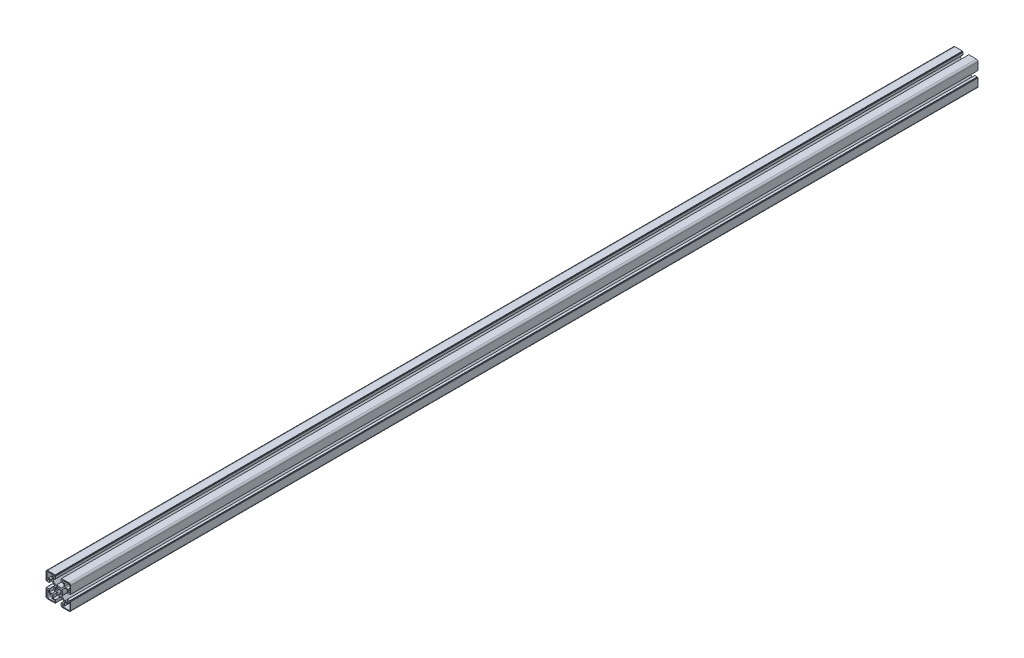
SolidWorks part; units mm, degrees
ref_plane "Front Plane" through (0, 0, 0) normal (0, 0, 1) x (1, 0, 0)
ref_plane "Top Plane" through (0, 0, 0) normal (0, 1, 0) x (1, 0, 0)
ref_plane "Right Plane" through (0, 0, 0) normal (1, 0, 0) x (0, 0, -1)
sketch "Sketch1" plane through (0, 0, 0) normal (0, 0, 1) x (1, 0, 0)
  line L2 (-19.5072, 22.5044) -> (-5.7912, 22.5044)
  line L3 (-5.7912, 22.5044) -> (-5.7912, 21.0058)
  line L4 (-5.7912, 21.0058) -> (-5.0038, 21.0058)
  line L6 (-5.0038, 21.0058) -> (-5.0038, 16.51)
  line L7 (-5.0038, 16.51) -> (-10.0457, 16.51)
  line L8 (-10.0457, 16.51) -> (-10.0457, 11.6801)
  line L9 (-10.0457, 11.6801) -> (-4.781, 6.4154)
  line L11 (-11.6801, 10.0457) -> (-6.4154, 4.781)
  line L12 (-16.51, 10.0457) -> (-11.6801, 10.0457)
  line L13 (-16.51, 5.0038) -> (-16.51, 10.0457)
  line L14 (-21.0058, 5.0038) -> (-16.51, 5.0038)
  line L15 (-21.0058, 5.7912) -> (-21.0058, 5.0038)
  line L16 (-22.5044, 5.7912) -> (-21.0058, 5.7912)
  line L17 (-22.5044, 19.5072) -> (-22.5044, 5.7912)
  line L18 (-18.0086, 11.5443) -> (-13.0429, 11.5443)
  line L19 (-18.0086, 11.5443) -> (-18.0086, 8.7884)
  line L20 (-11.5443, 18.0086) -> (-11.5443, 13.0429)
  line L21 (-21.0058, 19.5072) -> (-21.0058, 8.7884)
  line L23 (-11.5443, 18.0086) -> (-8.7884, 18.0086)
  line L24 (-19.5072, 21.0058) -> (-8.7884, 21.0058)
  line L25 (1.1893, 5.9789) -> (0.9762, 4.9077)
  line L26 (-1.1893, 5.9789) -> (-0.9762, 4.9077)
  line L27 (5.0686, 3.3868) -> (4.1605, 2.78)
  line L28 (3.3868, 5.0686) -> (2.78, 4.1605)
  line L29 (5.9789, -1.1893) -> (4.9077, -0.9762)
  line L30 (5.9789, 1.1893) -> (4.9077, 0.9762)
  line L31 (3.3868, -5.0686) -> (2.78, -4.1605)
  line L32 (5.0686, -3.3868) -> (4.1605, -2.78)
  line L33 (-1.1893, -5.9789) -> (-0.9762, -4.9077)
  line L34 (1.1893, -5.9789) -> (0.9762, -4.9077)
  line L35 (-5.0686, -3.3868) -> (-4.1605, -2.78)
  line L36 (-3.3868, -5.0686) -> (-2.78, -4.1605)
  line L37 (-5.9789, 1.1893) -> (-4.9077, 0.9762)
  line L38 (-5.9789, -1.1893) -> (-4.9077, -0.9762)
  line L39 (-3.3868, 5.0686) -> (-2.78, 4.1605)
  line L40 (-5.0686, 3.3868) -> (-4.1605, 2.78)
  line L41 (11.5443, 18.0086) -> (8.7884, 18.0086)
  line L42 (19.5072, 21.0058) -> (8.7884, 21.0058)
  line L43 (19.5072, 22.5044) -> (5.7912, 22.5044)
  line L44 (5.7912, 22.5044) -> (5.7912, 21.0058)
  line L45 (5.7912, 21.0058) -> (5.0038, 21.0058)
  line L46 (5.0038, 21.0058) -> (5.0038, 16.51)
  line L47 (5.0038, 16.51) -> (10.0457, 16.51)
  line L48 (10.0457, 16.51) -> (10.0457, 11.6801)
  line L49 (10.0457, 11.6801) -> (4.781, 6.4154)
  line L50 (11.6801, 10.0457) -> (6.4154, 4.781)
  line L51 (21.0058, 19.5072) -> (21.0058, 8.7884)
  line L52 (11.5443, 18.0086) -> (11.5443, 13.0429)
  line L53 (18.0086, 11.5443) -> (18.0086, 8.7884)
  line L54 (18.0086, 11.5443) -> (13.0429, 11.5443)
  line L55 (22.5044, 19.5072) -> (22.5044, 5.7912)
  line L56 (22.5044, 5.7912) -> (21.0058, 5.7912)
  line L57 (21.0058, 5.7912) -> (21.0058, 5.0038)
  line L58 (21.0058, 5.0038) -> (16.51, 5.0038)
  line L59 (16.51, 5.0038) -> (16.51, 10.0457)
  line L60 (16.51, 10.0457) -> (11.6801, 10.0457)
  line L61 (16.51, -10.0457) -> (11.6801, -10.0457)
  line L62 (16.51, -5.0038) -> (16.51, -10.0457)
  line L63 (21.0058, -5.0038) -> (16.51, -5.0038)
  line L64 (21.0058, -5.7912) -> (21.0058, -5.0038)
  line L65 (22.5044, -5.7912) -> (21.0058, -5.7912)
  line L66 (22.5044, -19.5072) -> (22.5044, -5.7912)
  line L67 (18.0086, -11.5443) -> (13.0429, -11.5443)
  line L68 (18.0086, -11.5443) -> (18.0086, -8.7884)
  line L69 (11.5443, -18.0086) -> (11.5443, -13.0429)
  line L70 (21.0058, -19.5072) -> (21.0058, -8.7884)
  line L71 (11.6801, -10.0457) -> (6.4154, -4.781)
  line L72 (10.0457, -11.6801) -> (4.781, -6.4154)
  line L73 (10.0457, -16.51) -> (10.0457, -11.6801)
  line L74 (5.0038, -16.51) -> (10.0457, -16.51)
  line L75 (5.0038, -21.0058) -> (5.0038, -16.51)
  line L76 (5.7912, -21.0058) -> (5.0038, -21.0058)
  line L77 (5.7912, -22.5044) -> (5.7912, -21.0058)
  line L78 (19.5072, -22.5044) -> (5.7912, -22.5044)
  line L79 (19.5072, -21.0058) -> (8.7884, -21.0058)
  line L80 (11.5443, -18.0086) -> (8.7884, -18.0086)
  line L81 (-11.5443, -18.0086) -> (-8.7884, -18.0086)
  line L82 (-19.5072, -21.0058) -> (-8.7884, -21.0058)
  line L83 (-19.5072, -22.5044) -> (-5.7912, -22.5044)
  line L84 (-5.7912, -22.5044) -> (-5.7912, -21.0058)
  line L85 (-5.7912, -21.0058) -> (-5.0038, -21.0058)
  line L86 (-5.0038, -21.0058) -> (-5.0038, -16.51)
  line L87 (-5.0038, -16.51) -> (-10.0457, -16.51)
  line L88 (-10.0457, -16.51) -> (-10.0457, -11.6801)
  line L89 (-10.0457, -11.6801) -> (-4.781, -6.4154)
  line L90 (-11.6801, -10.0457) -> (-6.4154, -4.781)
  line L91 (-21.0058, -19.5072) -> (-21.0058, -8.7884)
  line L92 (-11.5443, -18.0086) -> (-11.5443, -13.0429)
  line L93 (-18.0086, -11.5443) -> (-18.0086, -8.7884)
  line L94 (-18.0086, -11.5443) -> (-13.0429, -11.5443)
  line L95 (-22.5044, -19.5072) -> (-22.5044, -5.7912)
  line L96 (-22.5044, -5.7912) -> (-21.0058, -5.7912)
  line L97 (-21.0058, -5.7912) -> (-21.0058, -5.0038)
  line L98 (-21.0058, -5.0038) -> (-16.51, -5.0038)
  line L99 (-16.51, -5.0038) -> (-16.51, -10.0457)
  line L100 (-16.51, -10.0457) -> (-11.6801, -10.0457)
  arc A0 (-22.5044, 19.5072) -> (-19.5072, 22.5044) centre (-19.5072, 19.5072) cw
  arc A1 (-21.0058, 8.7884) -> (-18.0086, 8.7884) centre (-19.5072, 8.7884) ccw
  arc A2 (-21.0058, 19.5072) -> (-19.5072, 21.0058) centre (-19.5072, 19.5072) cw
  arc A3 (-8.7884, 21.0058) -> (-8.7884, 18.0086) centre (-8.7884, 19.5072) cw
  arc A4 (-11.5443, 13.0429) -> (-13.0429, 11.5443) centre (-13.0429, 13.0429) cw
  arc A5 (6.4154, -4.781) -> (6.4154, 4.781) centre (0, 0) ccw
  arc A6 (0.9762, 4.9077) -> (-0.9762, 4.9077) centre (0, 0) ccw
  arc A7 (-5.0686, 3.3868) -> (-5.9789, 1.1893) centre (0, 0) ccw
  arc A8 (4.1605, 2.78) -> (2.78, 4.1605) centre (0, 0) ccw
  arc A9 (4.9077, -0.9762) -> (4.9077, 0.9762) centre (0, 0) ccw
  arc A10 (2.78, -4.1605) -> (4.1605, -2.78) centre (0, 0) ccw
  arc A11 (-0.9762, -4.9077) -> (0.9762, -4.9077) centre (0, 0) ccw
  arc A12 (-4.1605, -2.78) -> (-2.78, -4.1605) centre (0, 0) ccw
  arc A13 (-4.9077, 0.9762) -> (-4.9077, -0.9762) centre (0, 0) ccw
  arc A14 (-2.78, 4.1605) -> (-4.1605, 2.78) centre (0, 0) ccw
  arc A15 (-5.9789, -1.1893) -> (-5.0686, -3.3868) centre (0, 0) ccw
  arc A16 (-3.3868, -5.0686) -> (-1.1893, -5.9789) centre (0, 0) ccw
  arc A17 (1.1893, -5.9789) -> (3.3868, -5.0686) centre (0, 0) ccw
  arc A18 (5.0686, -3.3868) -> (5.9789, -1.1893) centre (0, 0) ccw
  arc A19 (5.9789, 1.1893) -> (5.0686, 3.3868) centre (0, 0) ccw
  arc A20 (3.3868, 5.0686) -> (1.1893, 5.9789) centre (0, 0) ccw
  arc A21 (-1.1893, 5.9789) -> (-3.3868, 5.0686) centre (0, 0) ccw
  arc A22 (8.7884, 21.0058) -> (8.7884, 18.0086) centre (8.7884, 19.5072) ccw
  arc A23 (21.0058, 19.5072) -> (19.5072, 21.0058) centre (19.5072, 19.5072) ccw
  arc A24 (22.5044, 19.5072) -> (19.5072, 22.5044) centre (19.5072, 19.5072) ccw
  arc A25 (11.5443, 13.0429) -> (13.0429, 11.5443) centre (13.0429, 13.0429) ccw
  arc A26 (21.0058, 8.7884) -> (18.0086, 8.7884) centre (19.5072, 8.7884) cw
  arc A27 (21.0058, -8.7884) -> (18.0086, -8.7884) centre (19.5072, -8.7884) ccw
  arc A28 (11.5443, -13.0429) -> (13.0429, -11.5443) centre (13.0429, -13.0429) cw
  arc A29 (22.5044, -19.5072) -> (19.5072, -22.5044) centre (19.5072, -19.5072) cw
  arc A30 (21.0058, -19.5072) -> (19.5072, -21.0058) centre (19.5072, -19.5072) cw
  arc A31 (8.7884, -21.0058) -> (8.7884, -18.0086) centre (8.7884, -19.5072) cw
  arc A32 (-8.7884, -21.0058) -> (-8.7884, -18.0086) centre (-8.7884, -19.5072) ccw
  arc A33 (-21.0058, -19.5072) -> (-19.5072, -21.0058) centre (-19.5072, -19.5072) ccw
  arc A34 (-22.5044, -19.5072) -> (-19.5072, -22.5044) centre (-19.5072, -19.5072) ccw
  arc A35 (-11.5443, -13.0429) -> (-13.0429, -11.5443) centre (-13.0429, -13.0429) ccw
  arc A36 (-21.0058, -8.7884) -> (-18.0086, -8.7884) centre (-19.5072, -8.7884) cw
  arc A37 (4.781, 6.4154) -> (-4.781, 6.4154) centre (0, 0) ccw
  arc A38 (-4.781, -6.4154) -> (4.781, -6.4154) centre (0, 0) ccw
  arc A39 (-6.4154, 4.781) -> (-6.4154, -4.781) centre (0, 0) ccw
extrude "Boss-Extrude1" add sketch "Sketch1" along normal mid plane 1658.5
